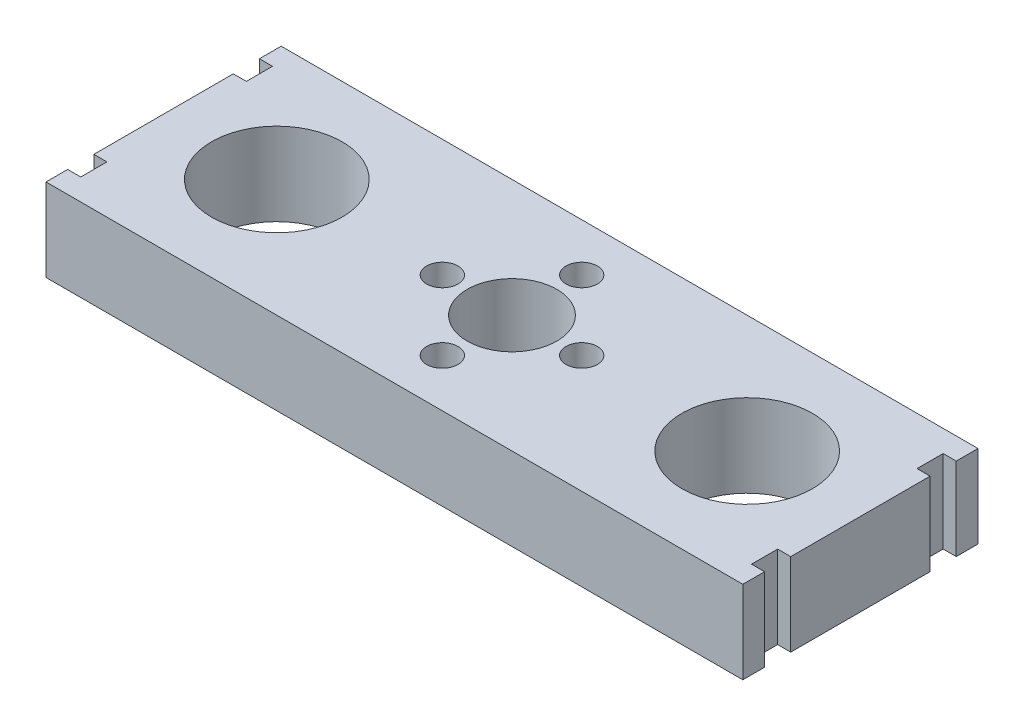
SolidWorks part; units mm, degrees
ref_plane "前视基准面" through (0, 0, 0) normal (0, 0, 1) x (1, 0, 0)
ref_plane "上视基准面" through (0, 0, 0) normal (0, 1, 0) x (1, 0, 0)
ref_plane "右视基准面" through (0, 0, 0) normal (1, 0, 0) x (0, 0, -1)
sketch "草图1" plane through (0, 0, 0) normal (0, 1, 0) x (1, 0, 0)
  line L1 (-40, 13.5) -> (40, 13.5)
  line L2 (-40, 13.5) -> (-40, -13.5)
  line L3 (-40, -13.5) -> (40, -13.5)
  line L4 (40, 13.5) -> (40, -13.5)
  line L5 (-40, 13.5) -> (40, -13.5) construction
  line L6 (-40, -13.5) -> (40, 13.5) construction
  point P0 (0, 0)
  dimension "D1" = 80
  dimension "D2" = 27
extrude "凸台-拉伸1" add sketch "草图1" along normal blind 9.5
sketch "草图2" plane through (0, 0, 0) normal (0, -1, 0) x (1, 0, 0)
  line L0 (-40, 0) -> (40, 0) construction
  line L1 (-40, -13.5) -> (-40, 13.5) construction
  line L2 (40, 13.5) -> (40, -13.5) construction
ref_plane "基准面1" through (0, 0, 0) normal (0, 0, 1) x (1, 0, 0)
sketch "草图3" plane through (0, 9.5, 0) normal (0, 1, 0) x (1, 0, 0)
  line L0 (-14.85, 0) -> (14.85, 0) construction
  line L1 (0, 13.5) -> (0, -13.5) construction
  line L2 (40, 13.5) -> (-40, 13.5) construction
  line L3 (-40, -13.5) -> (40, -13.5) construction
  circle A0 centre (-27, 0) radius 7.5
  circle A1 centre (27, 0) radius 7.5
  dimension "D1" = 15
  dimension "D2" = 54
extrude "切除-拉伸1" cut sketch "草图3" against normal through all contours A1 | A0
sketch "草图4" plane through (0, 9.5, 0) normal (0, 1, 0) x (1, 0, 0)
  line L0 (-40, 0) -> (40, 0) construction
  circle A0 centre (0, 0) radius 5.15
  dimension "D1" = 10.3
extrude "切除-拉伸2" cut sketch "草图4" against normal through all
sketch "草图5" plane through (0, 9.5, 0) normal (0, 1, 0) x (1, 0, 0)
  circle A4 centre (8, 0) radius 1.8
  circle A8 centre (-8, 0) radius 1.8
  circle A9 centre (0, 8) radius 1.8
  circle A10 centre (0, -8) radius 1.8
  dimension "D1" = 3.6
extrude "切除-拉伸3" cut sketch "草图5" against normal through all
ref_plane "基准面2" through (0, 4.5, 0) normal (0, 1, 0) x (1, 0, 0)
sketch "草图6" plane through (0, 4.5, 0) normal (0, 1, 0) x (1, 0, 0)
  line L0 (-40, 9.5) -> (40, 9.5) construction
  line L1 (-40, 13.5) -> (-40, -13.5) construction
  line L2 (40, -13.5) -> (40, 13.5) construction
  line L3 (-40, -9.5) -> (40, -9.5) construction
  line L4 (-40, -13.5) -> (40, -13.5) construction
  line L5 (40, 13.5) -> (-40, 13.5) construction
  dimension "D1" = 4
  dimension "D2" = 4
sketch "草图7" plane through (0, 9.5, 0) normal (0, 1, 0) x (1, 0, 0)
  line L0 (40, -13.5) -> (40, 13.5) construction
  line L1 (40, 11.0016) -> (38.5, 11.0016)
  line L2 (40, 11.0016) -> (40, 8.0016)
  line L3 (40, 8.0016) -> (38.5, 8.0016)
  line L4 (38.5, 11.0016) -> (38.5, 8.0016)
  line L13 (40, -7.9999) -> (38.5, -7.9999)
  line L14 (40, -7.9999) -> (40, -10.9999)
  line L15 (40, -10.9999) -> (38.5, -10.9999)
  line L16 (38.5, -7.9999) -> (38.5, -10.9999)
  line L17 (-40, 13.5) -> (-40, -13.5) construction
  line L18 (-40, 11.0016) -> (-38.5, 11.0016)
  line L19 (-40, 11.0016) -> (-40, 8.0016)
  line L20 (-40, 8.0016) -> (-38.5, 8.0016)
  line L21 (-38.5, 11.0016) -> (-38.5, 8.0016)
  line L23 (-40, -8.0068) -> (-38.5, -8.0068)
  line L24 (-40, -8.0068) -> (-40, -11.0068)
  line L25 (-40, -11.0068) -> (-38.5, -11.0068)
  line L26 (-38.5, -8.0068) -> (-38.5, -11.0068)
  point P20 (-40, -11.0068)
  dimension "D1" = 1.5
  dimension "D2" = 3
  dimension "D3" = 3
  dimension "D4" = 1.5
  dimension "D5" = 1.5
  dimension "D6" = 1.5
  dimension "D7" = 3
  dimension "D8" = 1.5
  dimension "D9" = 3
  dimension "D10" = 1.5
extrude "切除-拉伸4" cut sketch "草图7" against normal through all
